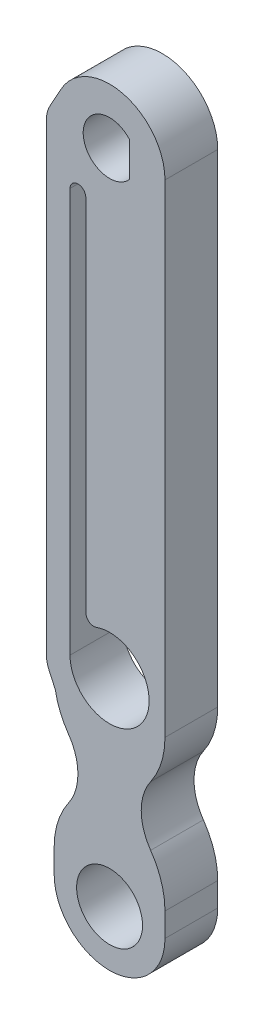
SolidWorks part; units mm, degrees
ref_plane "前视基准面" through (0, 0, 0) normal (0, 0, 1) x (1, 0, 0)
ref_plane "上视基准面" through (0, 0, 0) normal (0, 1, 0) x (1, 0, 0)
ref_plane "右视基准面" through (0, 0, 0) normal (1, 0, 0) x (0, 0, -1)
sketch "草图1" plane through (0, 0, 0) normal (0, 0, 1) x (1, 0, 0)
  line L0 (-3, 45.6431) -> (-3, 15)
  line L1 (-1.8, 18.3941) -> (-1.8, 45.6431)
  line L2 (1.5, 48.4771) -> (1.5, 51.1229)
  line L3 (-3.7053, 51.7775) -> (-4.4998, 50.3424)
  line L4 (-4.8, 49.1801) -> (-4.8, 14.2025)
  line L5 (-4.5818, 13.2027) -> (-4.1124, 12.1782)
  line L6 (-4.2, 1.8) -> (-4.2, 0)
  line L7 (4.2, 0) -> (4.2, 1.8)
  line L8 (4.2, 13.2) -> (4.2, 49.8)
  circle A0 centre (0, 0) radius 2.5
  arc A1 (-1.8, 18.3941) -> (-1, 17.8284) centre (-1.2, 18.3941) ccw
  arc A2 (-3, 15) -> (-1, 17.8284) centre (0, 15) ccw
  arc A3 (-1.8, 45.6431) -> (-3, 45.6431) centre (-2.4, 45.6431) ccw
  arc A4 (1.5, 51.1229) -> (1.5, 48.4771) centre (0, 49.8) ccw
  arc A5 (4.2, 49.8) -> (-3.7053, 51.7775) centre (0, 49.8) ccw
  arc A6 (-4.4998, 50.3424) -> (-4.8, 49.1801) centre (-2.4, 49.1801) ccw
  arc A7 (-4.8, 14.2025) -> (-4.5818, 13.2027) centre (-2.4, 14.2025) ccw
  arc A8 (-4.1124, 12.1782) -> (-3.1118, 9.7542) centre (1.8, 13.2) ccw
  arc A9 (-3.1118, 5.2458) -> (-3.1118, 9.7542) centre (-6.325, 7.5) ccw
  arc A10 (-3.1118, 5.2458) -> (-4.2, 1.8) centre (1.8, 1.8) ccw
  arc A11 (-4.2, 0) -> (4.2, 0) centre (0, 0) ccw
  arc A12 (4.2, 1.8) -> (3.1118, 5.2458) centre (-1.8, 1.8) ccw
  arc A13 (3.1118, 9.7542) -> (3.1118, 5.2458) centre (6.325, 7.5) ccw
  arc A14 (3.1118, 9.7542) -> (4.2, 13.2) centre (-1.8, 13.2) ccw
  point P34 (0, 0)
  dimension "D3" = 5
  dimension "D4" = 3
  dimension "D5" = 15
  dimension "D6" = 34.8
extrude "凸台-拉伸1" add sketch "草图1" along normal blind 4 contours L8 A5 L3 A6 L4 A7 L5 A8 A9 A10 L6 A11 L7 A12 A13 A14
